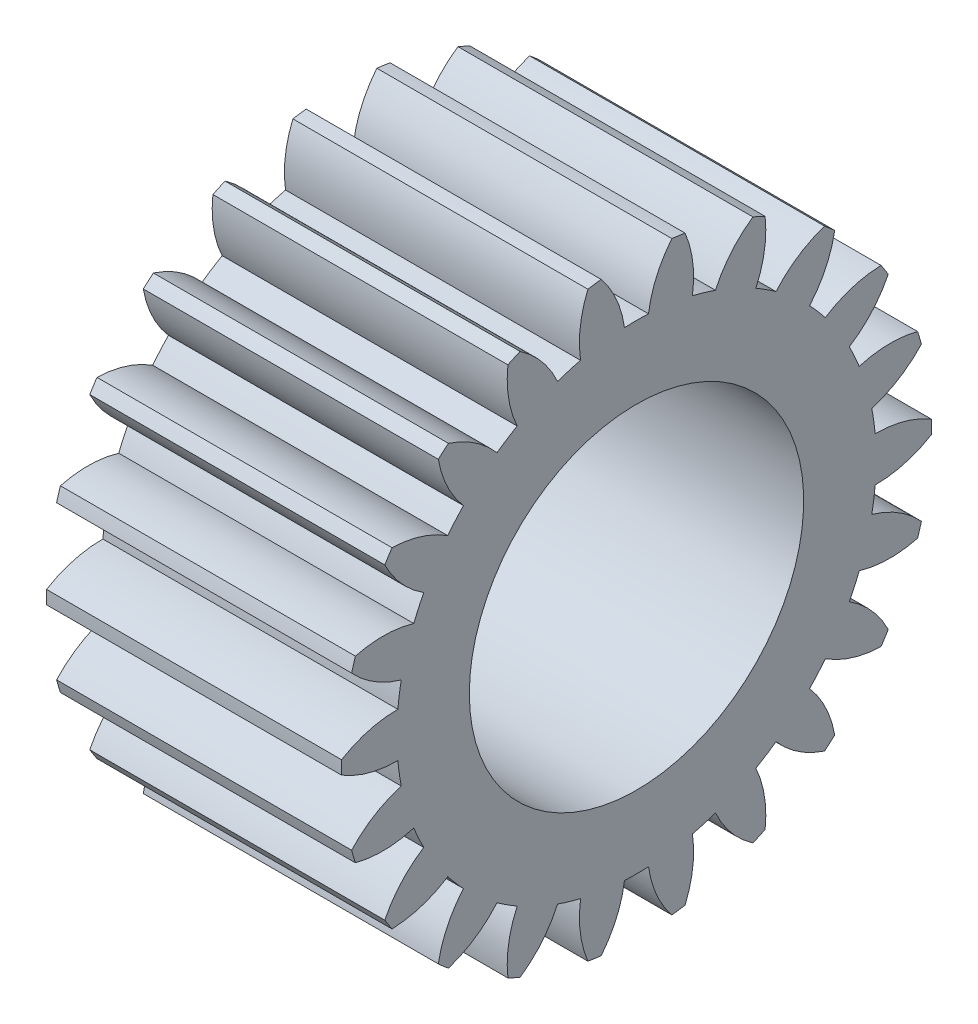
SolidWorks part; units mm, degrees
ref_plane "Plane1" through (0, 0, 0) normal (0, 0, 1) x (1, 0, 0)
ref_plane "Plane2" through (0, 0, 0) normal (0, 1, 0) x (1, 0, 0)
ref_plane "Plane3" through (0, 0, 0) normal (1, 0, 0) x (0, 0, -1)
sketch "HoldingSke" plane through (0, 0, 0) normal (0, 1, 0) x (1, 0, 0)
  line L0 (0, 0) -> (0.7417, -0.2997)
  line L1 (-15, 0) -> (100, 0) construction
  line L2 (0, 0) -> (-2.1039, 2.3779)
  line L3 (0, 0) -> (-11.863, 4.5341)
  line L4 (0, 0) -> (8.0072, 3.2351)
  line L5 (0, 0) -> (-46.8476, -17.4728)
  line L6 (0, 0) -> (-12.4344, -8.3896)
  line L7 (-2.1039, 2.3779) -> (8.6586, 51.2059)
  line L8 (-76.2, 54.61) -> (-73.4, 54.61)
  line L9 (-71.009, 38.7566) -> (-53.1078, 45.2721)
  line L10 (-76.2, 71.12) -> (104.1128, 71.12)
  line L11 (0, 0) -> (-15, 0)
  line L12 (-76.2, 101.6) -> (-76.155, 101.6)
  line L13 (24.9733, 27.94) -> (52.9518, 28.4284)
  line L14 (24.9733, 27.94) -> (24.9743, 27.94)
  line L15 (24.9733, 27.94) -> (100.4006, 29.5858)
  line L16 (-63.627, -1.25) -> (-12.827, -1.25)
  circle A0 centre (0, 0) radius 8.5
  circle A1 centre (0, 0) radius 12.1865
  circle A2 centre (0, 0) radius 37.5
  circle A3 centre (0, 0) radius 8.5
  dimension "MHD" = 24.373
  dimension "Hub_dia" = 75
  dimension "Bore" = 17
  dimension "MBD" = 17
  dimension "Num_teeth" = 22
  dimension "Pitch" = 0.8
  dimension "Overall_len" = 50
  dimension "Show_teeth" = 22
  dimension "Thickness" = 15
  dimension "OAL" = 50.0001
  dimension "T_dim" = 2.8
  dimension "Ap" = 20
  dimension "H" = 19.05
  dimension "Pitch_radius" = 180.3128
  dimension "Width" = 15
  dimension "Backlash" = 0.045
  dimension "Addendum_fac" = 1
  dimension "Dedendum_fac" = 1.25
  dimension "Clearance_fac" = 0.25
  dimension "Dedendum_add" = 0.001
  dimension "Module" = 1.25
sketch "BasProSke" plane through (0, 0, 0) normal (0, 1, 0) x (1, 0, 0)
  line L0 (-10, 0) -> (60, 0) construction
  line L1 (0, 0) -> (0, 15)
  line L2 (0, 0) -> (15, 0)
  line L3 (15, 0) -> (15, 15)
  line L4 (15, 15) -> (0, 15)
  dimension "Thickness" = 15
  dimension "Diameter" = 30
revolve "Base-Revolve" add sketch "BasProSke" angle 360 about L0
sketch "TooCutSke" plane through (0, 0, 0) normal (1, 0, 0) x (0, 0, -1)
  line L1 (0, 0) -> (0, 107) construction
  line L2 (0, 0) -> (-1.0596, 13.7091) construction
  line L3 (0, 0) -> (-3.9052, 27.1614) construction
  line L4 (-1.0596, 13.7091) -> (-1.9526, 13.5807) construction
  arc A0 (0.6099, 12.1712) -> (-0.6099, 12.1712) centre (0, 0) ccw
  arc A1 (1.8166, 14.9152) -> (-1.8166, 14.9152) centre (0, 0) ccw
  circle A2 centre (0, 0) radius 13.75 construction
  circle A3 centre (0, 0) radius 12.9208 construction
  arc A4 (-0.6099, 12.1712) -> (-1.8166, 14.9152) centre (-6.0574, 11.4129) ccw
  arc A5 (1.8166, 14.9152) -> (0.6099, 12.1712) centre (6.0574, 11.4129) ccw
  dimension "Root_dia" = 24.373
  dimension "Overcut_dia" = 30.0508
  dimension "Pitch_dia" = 27.5
  dimension "Base_dia" = 25.8415
  dimension "Flank_rad" = 5.5
  dimension "Half_ang" = 8.182
  dimension "Half_CT" = 0.9022
extrude "ToothCut" cut sketch "TooCutSke" along normal through all
fillet "Breaks" [suppressed] radius 0.025
fillet "RootFillets" [suppressed] radius 0.3135
pattern_circular "TeethCuts" count 22 every 16.364 about axis through (-10, 0, 0) along (1, 0, 0) of "ToothCut", "RootFillets", "Breaks"
sketch "HubNeaOneSke" plane through (0, 0, 0) normal (-1, 0, 0) x (0, 0, 1)
  circle A0 centre (0, 0) radius 12.1865
  dimension "Diameter" = 24.373
extrude "HubNearOne" [suppressed] add sketch "HubNeaOneSke" along normal blind 35.0001
sketch "HubNeaBotSke" plane through (0, 0, 0) normal (-1, 0, 0) x (0, 0, 1)
  circle A0 centre (0, 0) radius 12.1865
  dimension "Diameter" = 24.373
extrude "HubNearBoth" [suppressed] add sketch "HubNeaBotSke" along normal blind 17.5
ref_plane "FarPln" through (15, 0, 0) normal (1, 0, 0) x (0, 0, -1)
sketch "HubFarSke" plane through (15, 0, 0) normal (1, 0, 0) x (0, 0, -1)
  circle A0 centre (0, 0) radius 12.1865
  dimension "Diameter" = 24.373
extrude "HubFar" [suppressed] add sketch "HubFarSke" along normal blind 17.5
sketch "BorSke" plane through (0, 0, 0) normal (1, 0, 0) x (0, 0, -1)
  circle A0 centre (0, 0) radius 8.5
  dimension "Diameter" = 17
extrude "Bore" cut sketch "BorSke" along normal mid plane 100.0001
sketch "KeySke" plane through (0, 0, 0) normal (1, 0, 0) x (0, 0, -1)
  line L0 (-3, 0) -> (-3, 11.3)
  line L1 (-3, 11.3) -> (3, 11.3)
  line L2 (3, 11.3) -> (3, 0)
  line L3 (0, 0) -> (0, 34) construction
  line L4 (-3, 0) -> (3, 0)
  dimension "Offset" = 11.3
  dimension "Width" = 6
extrude "Keyway" [suppressed] cut sketch "KeySke" along normal mid plane 100.0001
pattern_circular "Keyway2" [suppressed] count 2 every 90 about axis through (-10, 0, 0) along (1, 0, 0)
sketch "Sketch2" plane through (15, 0, 0) normal (1, 0, 0) x (0, 0, -1)
  circle A0 centre (0, 0) radius 13.75
equation "' \"Module@HoldingSke\" = 6.35"
equation "' \"Num_teeth@HoldingSke\" = 12"
equation "' \"Ap@HoldingSke\" =  20"
equation "' \"Ap@HoldingSke\" = 20"
equation "' \"Width@HoldingSke\" = 0.5 * 25.4"
equation "' \"Hub_dia@HoldingSke\"= 1 * 25.4"
equation "' \"Hub_dia@HoldingSke\" = 1 * 25.4"
equation "' \"Overall_len@HoldingSke\" = 1.0 * 25.4"
equation "' \"Bore@HoldingSke\" = 0.75 * 25.4"
equation "' \"T_dim@HoldingSke\" = 0.1 * 25.4"
equation "' \"Width@KeySke\" = 0.25 * 25.4"
equation "' \"Show_teeth@HoldingSke\" = 13"
equation "' \"Backlash@HoldingSke\" = 0.009 * 25.4"
equation "' \"Addendum_fac@HoldingSke\" = 1.0"
equation "' \"Dedendum_fac@HoldingSke\" = 1.25"
equation "' \"Dedendum_add@HoldingSke\" = 0.00005 * 25.4"
equation "' \"Clearance_fac@HoldingSke\" = 0.25"
equation "\"Pitch@HoldingSke\" = 1 / \"Module@HoldingSke\""
equation "\"Overcut_dia@TooCutSke\" = (\"Num_teeth@HoldingSke\" + 2 * \"Addendum_fac@HoldingSke\") / \"Pitch@HoldingSke\" + 0.002 * 25.4"
equation "\"Pitch_dia@TooCutSke\" = \"Num_teeth@HoldingSke\" / \"Pitch@HoldingSke\""
equation "\"Base_dia@TooCutSke\" = \"Num_teeth@HoldingSke\" / \"Pitch@HoldingSke\" * cos((\"Ap@HoldingSke\"  * 3.14159265 / 180))"
equation "\"Root_dia@TooCutSke\" = (\"Num_teeth@HoldingSke\" + 2) / \"Pitch@HoldingSke\" - 2 * (\"Addendum_fac@HoldingSke\" + \"Dedendum_fac@HoldingSke\") / \"Pitch@HoldingSke\" - \"Dedendum_add@HoldingSke\" * 2"
equation "\"Half_ang@TooCutSke\" = 180 / \"Num_teeth@HoldingSke\""
equation "\"Half_CT@TooCutSke\" = \"Num_teeth@HoldingSke\" / \"Pitch@HoldingSke\" * sin((3.14159265 / 2 / \"Num_teeth@HoldingSke\")) / 2 - 7 * \"Backlash@HoldingSke\" / 4"
equation "\"Flank_rad@TooCutSke\" = \"Num_teeth@HoldingSke\" / \"Pitch@HoldingSke\" / 5"
equation "\"Radius@RootFillets\" = \"Clearance_fac@HoldingSke\" / \"Pitch@HoldingSke\" + \"Dedendum_add@HoldingSke\""
equation "\"Break_rad@Breaks\" = 0.02 / \"Pitch@HoldingSke\""
equation "\"Thickness@HoldingSke\" = \"Width@HoldingSke\""
equation "\"OAL@HoldingSke\" = \"Thickness@HoldingSke\""
equation "\"MHD@HoldingSke\" = (\"Num_teeth@HoldingSke\" + 2) / \"Pitch@HoldingSke\" - 2 * (\"Addendum_fac@HoldingSke\" + \"Dedendum_fac@HoldingSke\")  / \"Pitch@HoldingSke\" - \"Dedendum_add@HoldingSke\" * 2"
equation "\"MBD@HoldingSke\" = (\"Num_teeth@HoldingSke\" + 2) / \"Pitch@HoldingSke\" - 2 * (\"Addendum_fac@HoldingSke\" + \"Dedendum_fac@HoldingSke\")  / \"Pitch@HoldingSke\" - \"Dedendum_add@HoldingSke\" * 2 - 0.002 * 25.4"
equation "\"MHD@HoldingSke\" = ((sgn( \"MHD@HoldingSke\" - \"Hub_dia@HoldingSke\" )-1)*( \"MHD@HoldingSke\" - \"Hub_dia@HoldingSke\" ))/-2+ \"Hub_dia@HoldingSke\""
equation "\"MBD@HoldingSke\" = ((sgn( \"MBD@HoldingSke\" - \"Bore@HoldingSke\" )-1)*( \"MBD@HoldingSke\" - \"Bore@HoldingSke\" ))/-2+ \"Bore@HoldingSke\""
equation "\"OAL@HoldingSke\" = ((sgn( \"OAL@HoldingSke\" - \"Overall_len@HoldingSke\" )+1)*( \"OAL@HoldingSke\" - \"Overall_len@HoldingSke\" ))/2 + \"Overall_len@HoldingSke\" + 0.000002 * 25.4"
equation "\"Num_teeth@TeethCuts\" = int( \"Show_teeth@HoldingSke\" ) + 1"
equation "\"Num_teeth@TeethCuts\" = ((sgn( \"Num_teeth@TeethCuts\" - \"Num_teeth@HoldingSke\" )-1)*( \"Num_teeth@TeethCuts\" - \"Num_teeth@HoldingSke\" ))/-2+ \"Num_teeth@HoldingSke\""
equation "\"Num_teeth@TeethCuts\" = ((sgn( \"Num_teeth@TeethCuts\" - 2.0)+1)*( \"Num_teeth@TeethCuts\" - 2.0))/2 +2.0"
equation "\"Angle@TeethCuts\" = 360.0 / \"Num_teeth@HoldingSke\""
equation "\"Diameter@BasProSke\" = (\"Num_teeth@HoldingSke\" + 2 * \"Addendum_fac@HoldingSke\") / \"Pitch@HoldingSke\""
equation "\"Thickness@BasProSke\"  = \"Thickness@HoldingSke\""
equation "' \"Fillet_rad@BasProSke\" =  \"Thickness@HoldingSke\" * 0.05"
equation "' \"Fillet_rad@BasProSke\" = \"Thickness@HoldingSke\" * 0.05"
equation "\"MHD@HoldingSke\" = ((sgn( \"MHD@HoldingSke\" - \"Root_dia@TooCutSke\" )-1)*( \"MHD@HoldingSke\" - \"Root_dia@TooCutSke\" ))/-2+ \"Root_dia@TooCutSke\""
equation "\"Diameter@HubNeaOneSke\" = \"MHD@HoldingSke\""
equation "\"Length@HubNearOne\" = \"OAL@HoldingSke\" - \"Thickness@BasProSke\""
equation "\"Diameter@HubNeaBotSke\" = \"MHD@HoldingSke\""
equation "\"Length@HubNearBoth\" = ( \"OAL@HoldingSke\" - \"Thickness@BasProSke\" ) / 2.0"
equation "\"Thickness@FarPln\" = \"Thickness@BasProSke\""
equation "\"Diameter@HubFarSke\" = \"MHD@HoldingSke\""
equation "\"Length@HubFar\" = ( \"OAL@HoldingSke\" - \"Thickness@BasProSke\" ) / 2.0"
equation "\"Diameter@BorSke\" = \"MBD@HoldingSke\""
equation "\"D1@Bore\" = \"OAL@HoldingSke\" * 2.0"
equation "\"D1@Keyway\" = \"OAL@HoldingSke\" * 2.0"
equation "\"Offset@KeySke\" = \"T_dim@HoldingSke\" + \"MBD@HoldingSke\" / 2.0"
